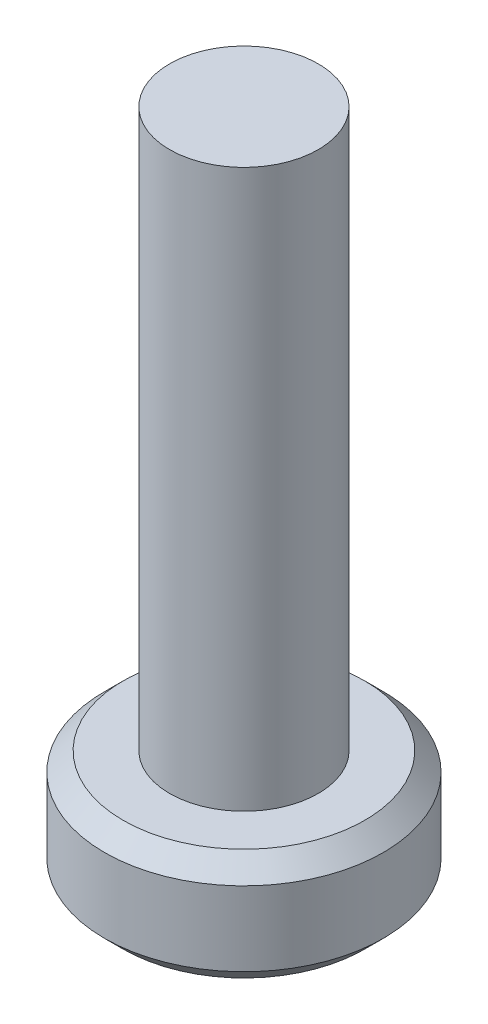
SolidWorks part; units mm, degrees
ref_plane "前视基准面" through (0, 0, 0) normal (0, 0, 1) x (1, 0, 0)
ref_plane "上视基准面" through (0, 0, 0) normal (0, 1, 0) x (1, 0, 0)
ref_plane "右视基准面" through (0, 0, 0) normal (1, 0, 0) x (0, 0, -1)
sketch "草图1" plane through (0, 0, 0) normal (0, 1, 0) x (1, 0, 0)
  circle A0 centre (0, 0) radius 3.75
  dimension "D1" = 7.5
extrude "凸台-拉伸1" add sketch "草图1" along normal blind 3
sketch "草图2" plane through (0, 3, 0) normal (0, 1, 0) x (1, 0, 0)
  circle A0 centre (0, 0) radius 2
  dimension "D1" = 4
extrude "凸台-拉伸2" add sketch "草图2" along normal blind 15
chamfer "倒角1" distance 0.5 angle 45 2 edges at (0, 3, 3.75) (0, 0, 3.75)
sketch "草图3" plane through (0, 0, 0) normal (0, -1, 0) x (1, 0, 0)
  line L1 (0, -2.8868) -> (2.5, -1.4434)
  line L2 (2.5, -1.4434) -> (2.5, 1.4434)
  line L3 (2.5, 1.4434) -> (0, 2.8868)
  line L4 (0, 2.8868) -> (-2.5, 1.4434)
  line L5 (-2.5, 1.4434) -> (-2.5, -1.4434)
  line L6 (-2.5, -1.4434) -> (0, -2.8868)
  circle A0 centre (0, 0) radius 2.5 construction
  dimension "D1" = 5
extrude "切除-拉伸1" cut sketch "草图3" against normal blind 1
